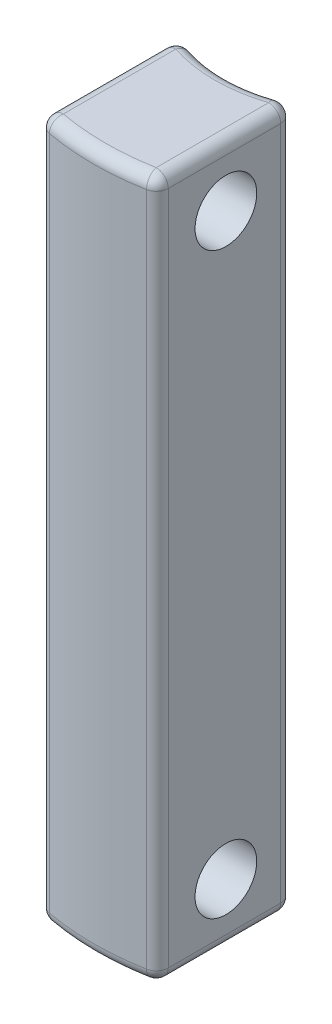
SolidWorks part; units mm, degrees
material "ABS"
ref_plane "Front Plane" through (0, 0, 0) normal (0, 0, 1) x (1, 0, 0)
ref_plane "Top Plane" through (0, 0, 0) normal (0, 1, 0) x (1, 0, 0)
ref_plane "Right Plane" through (0, 0, 0) normal (1, 0, 0) x (0, 0, -1)
sketch "Sketch1" plane through (0, 0, 0) normal (0, 1, 0) x (1, 0, 0)
  line L0 (-6.1595, 0) -> (6.1595, 0) construction
  line L1 (6.1595, 0) -> (6.1595, -12.9901) construction
  line L2 (-6.1595, 0) -> (-6.1595, -12.9901) construction
  line L3 (6.1595, -12.9901) -> (6.1595, -27.7472)
  line L4 (-6.1595, -12.9901) -> (-6.1595, -27.7472)
  arc A0 (-6.1595, -27.7472) -> (6.1595, -27.7472) centre (0, 0) ccw
  arc A1 (-6.1595, -12.9901) -> (6.1595, -12.9901) centre (0, 0) ccw
  dimension "D1" = 56.8452
  dimension "D2" = 28.7528
  dimension "D3" = 12.319
extrude "Boss-Extrude1" add sketch "Sketch1" along normal blind 19.05 and the other way blind 54.61
sketch "Sketch2" plane through (0, 0, 0) normal (1, 0, 0) x (0, 0, -1)
  line L0 (0, 0) -> (-20.6375, 0) construction
  line L1 (-20.6375, 0) -> (-20.6375, 12.7) construction
  line L2 (-20.6375, 0) -> (-20.6375, -48.26) construction
  line L4 (-20.6375, -48.26) -> (-20.6375, -54.61) construction
  line L5 (-27.7472, -54.61) -> (-12.9901, -54.61) construction
  line L6 (-20.6375, 12.7) -> (-20.6375, 19.05) construction
  line L7 (-27.7472, 19.05) -> (-12.9901, 19.05) construction
  circle A0 centre (-20.6375, 12.7) radius 3.2512
  circle A1 centre (-20.6375, -48.26) radius 3.2512
  dimension "D3" = 6.5024
  dimension "D1" = 20.6375
  dimension "D2" = 12.7
extrude "Cut-Extrude1" cut sketch "Sketch2" against normal mid plane 19.05
fillet "Fillet1" radius 1.27 12 edges at (0, 19.05, 14.3764) (0, 19.05, 28.4226) (0, -54.61, 14.3764) (0, -54.61, 28.4226) (-6.1595, 19.05, 20.3686) (6.1595, 19.05, 20.3686) (-6.1595, -54.61, 20.3686) (6.1595, -54.61, 20.3686) (-6.1595, -17.78, 12.9901) (-6.1595, -17.78, 27.7472) (6.1595, -17.78, 27.7472) (6.1595, -17.78, 12.9901)
